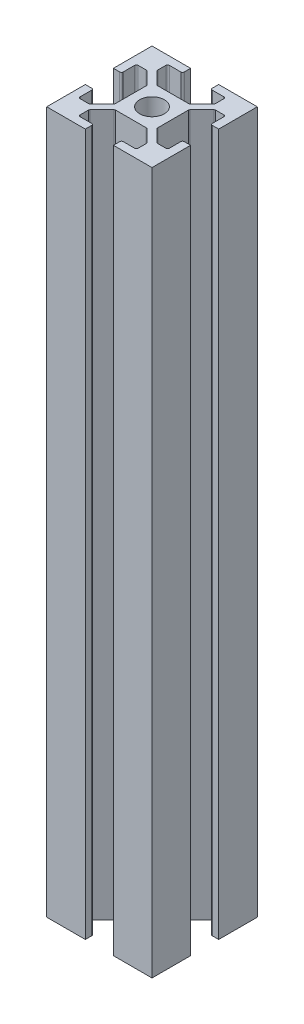
SolidWorks part; units mm, degrees
ref_plane "Alzado" through (0, 0, 0) normal (0, 0, 1) x (1, 0, 0)
ref_plane "Planta" through (0, 0, 0) normal (0, 1, 0) x (1, 0, 0)
ref_plane "Vista lateral" through (0, 0, 0) normal (1, 0, 0) x (0, 0, -1)
sketch "Croquis1" plane through (0, 0, 0) normal (0, 1, 0) x (1, 0, 0)
  line L1 (-15, 15) -> (15, 15)
  line L2 (-15, 15) -> (-15, -15)
  line L3 (-15, -15) -> (15, -15)
  line L4 (15, 15) -> (15, -15)
  line L5 (-15, 15) -> (15, -15) construction
  line L6 (-15, -15) -> (15, 15) construction
  point P0 (0, 0)
  dimension "D1" = 30
extrude "Saliente-Extruir1" add sketch "Croquis1" along normal blind 200
sketch "Croquis3" plane through (0, 200, 0) normal (0, 1, 0) x (1, 0, 0)
  line L0 (0, 15) -> (0, 0) construction
  line L1 (15, 15) -> (-15, 15) construction
  line L2 (4, 15) -> (-4, 15)
  line L3 (-4, 15) -> (-4, 13.2)
  line L4 (-4.5, 12.7) -> (-7.75, 12.7)
  line L5 (-8.25, 12.2) -> (-8.25, 9.9071)
  line L6 (-8.1036, 9.5536) -> (-4.6964, 6.1464)
  line L7 (-4.3429, 6) -> (4.3429, 6)
  line L8 (8.1036, 9.5536) -> (4.6964, 6.1464)
  line L9 (8.25, 12.2) -> (8.25, 9.9071)
  line L10 (4.5, 12.7) -> (7.75, 12.7)
  line L11 (4, 15) -> (4, 13.2)
  line L12 (6, 4.3429) -> (6, -4.3429)
  line L13 (9.5536, -8.1036) -> (6.1464, -4.6964)
  line L14 (12.2, -8.25) -> (9.9071, -8.25)
  line L15 (12.7, -4.5) -> (12.7, -7.75)
  line L16 (15, -4) -> (13.2, -4)
  line L17 (15, -4) -> (15, 4)
  line L18 (15, 4) -> (13.2, 4)
  line L19 (12.7, 4.5) -> (12.7, 7.75)
  line L20 (12.2, 8.25) -> (9.9071, 8.25)
  line L21 (9.5536, 8.1036) -> (6.1464, 4.6964)
  line L22 (4.3429, -6) -> (-4.3429, -6)
  line L23 (-8.1036, -9.5536) -> (-4.6964, -6.1464)
  line L24 (-8.25, -12.2) -> (-8.25, -9.9071)
  line L25 (-4.5, -12.7) -> (-7.75, -12.7)
  line L26 (-4, -15) -> (-4, -13.2)
  line L27 (-4, -15) -> (4, -15)
  line L28 (4, -15) -> (4, -13.2)
  line L29 (4.5, -12.7) -> (7.75, -12.7)
  line L30 (8.25, -12.2) -> (8.25, -9.9071)
  line L31 (8.1036, -9.5536) -> (4.6964, -6.1464)
  line L32 (-6, -4.3429) -> (-6, 4.3429)
  line L33 (-9.5536, 8.1036) -> (-6.1464, 4.6964)
  line L34 (-12.2, 8.25) -> (-9.9071, 8.25)
  line L35 (-12.7, 4.5) -> (-12.7, 7.75)
  line L36 (-15, 4) -> (-13.2, 4)
  line L37 (-15, 4) -> (-15, -4)
  line L38 (-15, -4) -> (-13.2, -4)
  line L39 (-12.7, -4.5) -> (-12.7, -7.75)
  line L40 (-12.2, -8.25) -> (-9.9071, -8.25)
  line L41 (-9.5536, -8.1036) -> (-6.1464, -4.6964)
  arc A0 (4.5, 12.7) -> (4, 13.2) centre (4.5, 13.2) cw
  arc A1 (8.25, 12.2) -> (7.75, 12.7) centre (7.75, 12.2) ccw
  arc A2 (8.1036, 9.5536) -> (8.25, 9.9071) centre (7.75, 9.9071) ccw
  arc A3 (4.6964, 6.1464) -> (4.3429, 6) centre (4.3429, 6.5) cw
  arc A4 (-4.6964, 6.1464) -> (-4.3429, 6) centre (-4.3429, 6.5) ccw
  arc A5 (-8.25, 9.9071) -> (-8.1036, 9.5536) centre (-7.75, 9.9071) ccw
  arc A6 (-7.75, 12.7) -> (-8.25, 12.2) centre (-7.75, 12.2) ccw
  arc A7 (-4, 13.2) -> (-4.5, 12.7) centre (-4.5, 13.2) cw
  arc A8 (6.1464, 4.6964) -> (6, 4.3429) centre (6.5, 4.3429) ccw
  arc A9 (6.1464, -4.6964) -> (6, -4.3429) centre (6.5, -4.3429) cw
  arc A10 (9.5536, -8.1036) -> (9.9071, -8.25) centre (9.9071, -7.75) ccw
  arc A11 (12.2, -8.25) -> (12.7, -7.75) centre (12.2, -7.75) ccw
  arc A12 (12.7, -4.5) -> (13.2, -4) centre (13.2, -4.5) cw
  arc A13 (13.2, 4) -> (12.7, 4.5) centre (13.2, 4.5) cw
  arc A14 (12.7, 7.75) -> (12.2, 8.25) centre (12.2, 7.75) ccw
  arc A15 (9.9071, 8.25) -> (9.5536, 8.1036) centre (9.9071, 7.75) ccw
  arc A16 (4.6964, -6.1464) -> (4.3429, -6) centre (4.3429, -6.5) ccw
  arc A17 (-4.6964, -6.1464) -> (-4.3429, -6) centre (-4.3429, -6.5) cw
  arc A18 (-8.1036, -9.5536) -> (-8.25, -9.9071) centre (-7.75, -9.9071) ccw
  arc A19 (-8.25, -12.2) -> (-7.75, -12.7) centre (-7.75, -12.2) ccw
  arc A20 (-4.5, -12.7) -> (-4, -13.2) centre (-4.5, -13.2) cw
  arc A21 (4, -13.2) -> (4.5, -12.7) centre (4.5, -13.2) cw
  arc A22 (7.75, -12.7) -> (8.25, -12.2) centre (7.75, -12.2) ccw
  arc A23 (8.25, -9.9071) -> (8.1036, -9.5536) centre (7.75, -9.9071) ccw
  arc A24 (-6.1464, -4.6964) -> (-6, -4.3429) centre (-6.5, -4.3429) ccw
  arc A25 (-6.1464, 4.6964) -> (-6, 4.3429) centre (-6.5, 4.3429) cw
  arc A26 (-9.5536, 8.1036) -> (-9.9071, 8.25) centre (-9.9071, 7.75) ccw
  arc A27 (-12.2, 8.25) -> (-12.7, 7.75) centre (-12.2, 7.75) ccw
  arc A28 (-12.7, 4.5) -> (-13.2, 4) centre (-13.2, 4.5) cw
  arc A29 (-13.2, -4) -> (-12.7, -4.5) centre (-13.2, -4.5) cw
  arc A30 (-12.7, -7.75) -> (-12.2, -8.25) centre (-12.2, -7.75) ccw
  arc A31 (-9.9071, -8.25) -> (-9.5536, -8.1036) centre (-9.9071, -7.75) ccw
  circle A32 centre (0, 0) radius 3.5
  point P12 (0, 6)
  point P18 (4, 12.7)
  point P21 (8.25, 12.7)
  point P24 (8.25, 9.7)
  point P27 (4.55, 6)
  point P30 (-4.55, 6)
  point P33 (-8.25, 9.7)
  point P36 (-8.25, 12.7)
  point P39 (-4, 12.7)
  point P121 (0, 0)
  dimension "D7" = 0.5
  dimension "D9" = 7
  dimension "D1" = 4
  dimension "D2" = 8.25
  dimension "D3" = 6
  dimension "D4" = 135
  dimension "D5" = 2.3
  dimension "D6" = 3
  dimension "D8" = 4
extrude "Cortar-Extruir2" cut sketch "Croquis3" against normal through all
sketch "Croquis4" plane through (0, 200, 0) normal (0, 1, 0) x (1, 0, 0)
  line L0 (0, 0) -> (0, -6) construction
  line L1 (-12.1, 13.7) -> (-9.9, 13.7)
  line L2 (-13.1, 12.7) -> (-13.1, 9.9)
  line L3 (-12.7, 9.5) -> (-9.9, 9.5)
  line L4 (-9.5, 13.3) -> (-9.5, 9.9)
  line L5 (-13.1, 13.7) -> (-9.5, 9.5) construction
  line L6 (-13.1, 9.5) -> (-9.5, 13.7) construction
  line L7 (4.3429, -6) -> (-4.3429, -6) construction
  line L8 (0, 0) -> (-6, 0) construction
  line L9 (-6, -4.3429) -> (-6, 4.3429) construction
  line L10 (12.7, 9.5) -> (9.9, 9.5)
  line L11 (9.5, 13.3) -> (9.5, 9.9)
  line L12 (12.1, 13.7) -> (9.9, 13.7)
  line L13 (13.1, 12.7) -> (13.1, 9.9)
  line L14 (-13.1, -9.5) -> (-9.5, -13.7) construction
  line L15 (-13.1, -13.7) -> (-9.5, -9.5) construction
  line L16 (13.1, -12.7) -> (13.1, -9.9)
  line L17 (12.1, -13.7) -> (9.9, -13.7)
  line L18 (9.5, -13.3) -> (9.5, -9.9)
  line L19 (12.7, -9.5) -> (9.9, -9.5)
  line L20 (-9.5, -13.3) -> (-9.5, -9.9)
  line L21 (-12.7, -9.5) -> (-9.9, -9.5)
  line L22 (-13.1, -12.7) -> (-13.1, -9.9)
  line L23 (-12.1, -13.7) -> (-9.9, -13.7)
  arc A0 (-13.1, 9.9) -> (-12.7, 9.5) centre (-12.7, 9.9) ccw
  arc A1 (-9.9, 9.5) -> (-9.5, 9.9) centre (-9.9, 9.9) ccw
  arc A2 (-9.9, 13.7) -> (-9.5, 13.3) centre (-9.9, 13.3) cw
  arc A3 (-12.1, 13.7) -> (-13.1, 12.7) centre (-12.1, 12.7) ccw
  arc A4 (9.9, 9.5) -> (9.5, 9.9) centre (9.9, 9.9) cw
  arc A5 (9.9, 13.7) -> (9.5, 13.3) centre (9.9, 13.3) ccw
  arc A6 (13.1, 9.9) -> (12.7, 9.5) centre (12.7, 9.9) cw
  arc A7 (12.1, 13.7) -> (13.1, 12.7) centre (12.1, 12.7) cw
  arc A8 (12.1, -13.7) -> (13.1, -12.7) centre (12.1, -12.7) ccw
  arc A9 (13.1, -9.9) -> (12.7, -9.5) centre (12.7, -9.9) ccw
  arc A10 (9.9, -13.7) -> (9.5, -13.3) centre (9.9, -13.3) cw
  arc A11 (9.9, -9.5) -> (9.5, -9.9) centre (9.9, -9.9) ccw
  arc A12 (-12.1, -13.7) -> (-13.1, -12.7) centre (-12.1, -12.7) cw
  arc A13 (-9.9, -13.7) -> (-9.5, -13.3) centre (-9.9, -13.3) ccw
  arc A14 (-9.9, -9.5) -> (-9.5, -9.9) centre (-9.9, -9.9) cw
  arc A15 (-13.1, -9.9) -> (-12.7, -9.5) centre (-12.7, -9.9) cw
  point P0 (-11.3, 11.6)
  point P65 (-11.3, -11.6)
  dimension "D4" = 0.4
  dimension "D5" = 1
  dimension "D1" = 4.2
  dimension "D2" = 9.5
  dimension "D3" = 9.5
extrude "Cortar-Extruir3" [suppressed] cut sketch "Croquis4" against normal through all
